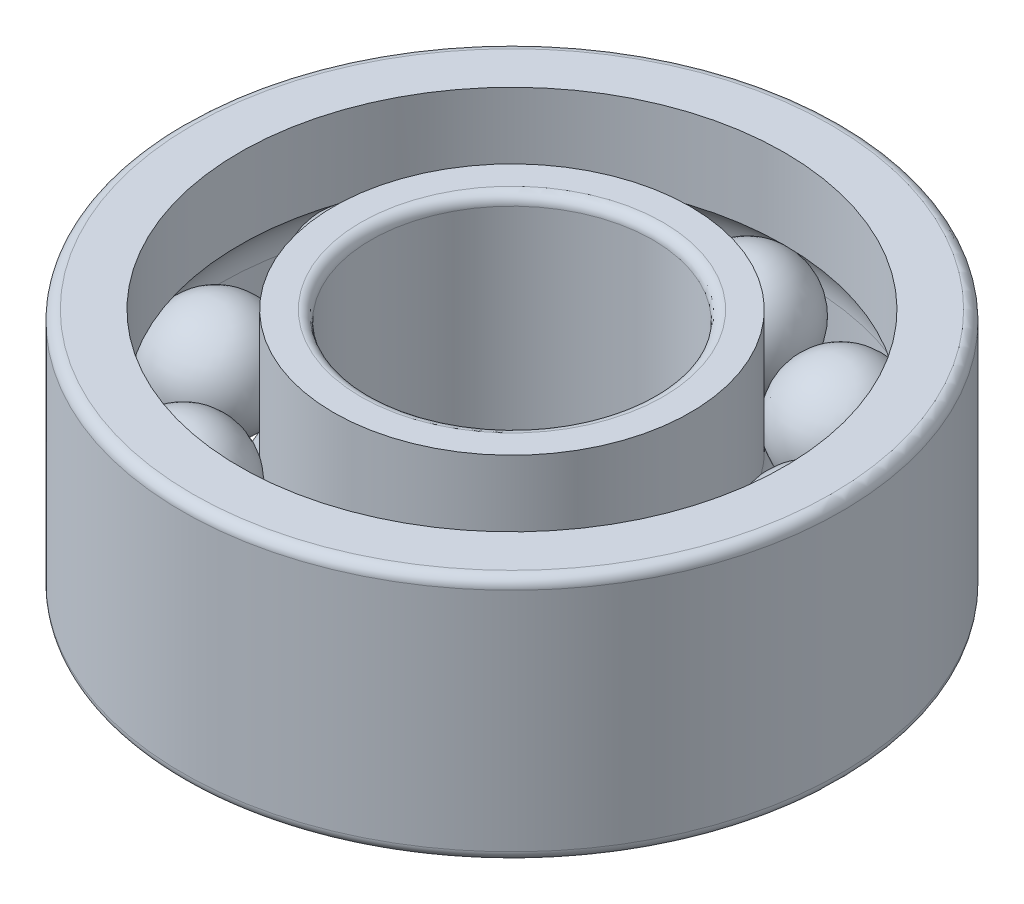
SolidWorks part; units mm, degrees
ref_plane "Front Plane" through (0, 0, 0) normal (0, 0, 1) x (1, 0, 0)
ref_plane "Top Plane" through (0, 0, 0) normal (0, 1, 0) x (1, 0, 0)
ref_plane "Right Plane" through (0, 0, 0) normal (1, 0, 0) x (0, 0, -1)
sketch "Sketch1" plane through (0, 0, 0) normal (1, 0, 0) x (0, 0, -1)
  line L0 (-16, 12.85) -> (-16, -12.85)
  line L1 (-16, 14) -> (16, 14) construction
  line L2 (-16, 14) -> (-16, -14) construction
  line L3 (-16, -14) -> (16, -14) construction
  line L4 (16, 14) -> (16, -14) construction
  line L5 (-16, 14) -> (16, -14) construction
  line L6 (-16, -14) -> (16, 14) construction
  line L7 (-17.15, -14) -> (-22.5, -14)
  line L8 (-22.5, -14) -> (-22.5, -4.9181)
  line L9 (-17.15, 14) -> (-20.25, 14)
  line L10 (-20.25, 14) -> (-20.25, 0)
  line L11 (0, 0) -> (26.7, 0) construction
  line L12 (0, 0) -> (0, 11.0701) construction
  arc A0 (-20.25, 0) -> (-22.5, -4.9181) centre (-26.75, 0) cw
  arc A2 (-16, -12.85) -> (-17.15, -14) centre (-17.15, -12.85) cw
  arc A3 (-16, 12.85) -> (-17.15, 14) centre (-17.15, 12.85) ccw
  point P0 (0, 0)
  dimension "D5" = 6.5
  dimension "D6" = 26.7
  dimension "D8" = 1.15
  dimension "D1" = 32
  dimension "D2" = 28
  dimension "D3" = 4.25
  dimension "D4" = 6.5
revolve "Revolve1" add sketch "Sketch1" angle 360 about L12
sketch "Sketch2" plane through (0, 0, 0) normal (1, 0, 0) x (0, 0, -1)
  line L0 (-26.7, 6.45) -> (-26.7, -6.45)
  circle A0 centre (-26.7, 0) radius 6.45 construction
  arc A1 (-26.7, -6.45) -> (-26.7, 6.45) centre (-26.7, 0) cw
  dimension "D1" = 12.9
  dimension "D2" = 26.7
revolve "Revolve4" add sketch "Sketch2" angle 360 about L0
pattern_circular "CirPattern1" count 10 over 360 about axis through (0, 0, 0) along (0, 1, 0) of bodies 107
sketch "Sketch3" plane through (0, 0, 0) normal (1, 0, 0) x (0, 0, -1)
  line L1 (-33.15, -14) -> (-36.25, -14)
  line L2 (-37.4, -12.85) -> (-37.4, 12.85)
  line L3 (-36.25, 14) -> (-30.9, 14)
  line L4 (-30.9, 14) -> (-30.9, 4.8952)
  line L6 (-33.15, 0) -> (-33.15, -14)
  line L7 (-22.5, -4.9181) -> (-22.5, -14) construction
  circle A0 centre (-26.7, 0) radius 6.45 construction
  arc A2 (-33.15, 0) -> (-30.9, 4.8952) centre (-26.65, -0.023) cw
  arc A3 (-36.25, -14) -> (-37.4, -12.85) centre (-36.25, -12.85) cw
  arc A4 (-37.4, 12.85) -> (-36.25, 14) centre (-36.25, 12.85) cw
  point P19 (-37.4, -14)
  point P22 (-37.4, 14)
  dimension "D3" = 10.65
  dimension "D1" = 6.5
  dimension "D5" = 1.15
  dimension "D2" = 4.25
  dimension "D4" = 6.5
revolve "Revolve5" add sketch "Sketch3" angle 360 about L12
